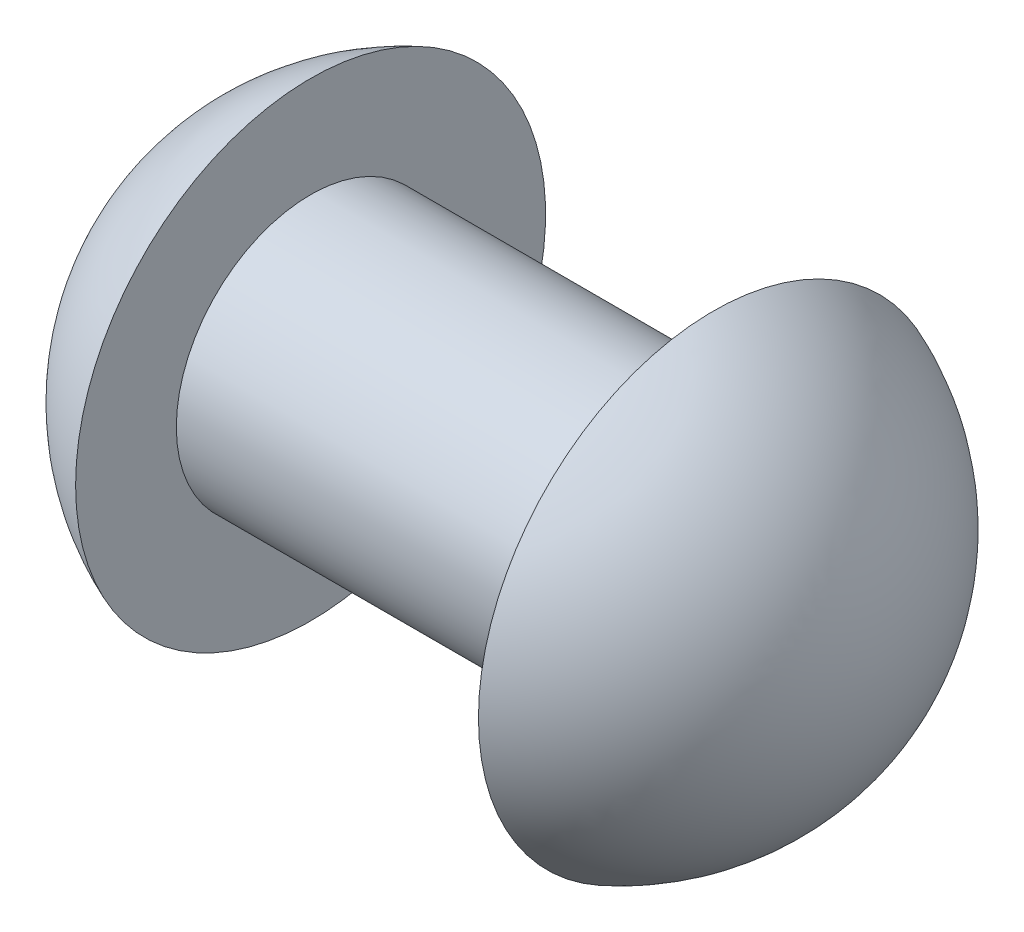
SolidWorks part; units mm, degrees
ref_plane "Plane1" through (0, 0, 0) normal (0, 0, 1) x (1, 0, 0)
ref_plane "Plane2" through (0, 0, 0) normal (0, 1, 0) x (1, 0, 0)
ref_plane "Plane3" through (0, 0, 0) normal (1, 0, 0) x (0, 0, -1)
sketch "Sketch1" plane through (0, 0, 0) normal (0, 0, 1) x (1, 0, 0)
  line L0 (-39, 0) -> (6, 0) construction
  line L1 (-4.2, 0) -> (0, 0)
  line L2 (-3, 1) -> (-3, 1.75)
  line L3 (-3, 1) -> (0, 1)
  line L4 (0, 1) -> (0, 0)
  arc A0 (-3, 1.75) -> (-4.2, 0) centre (-2.3001, -0.0164) ccw
  point P12 (-3, 1)
  dimension "HeadRadius" = 1.9
  dimension "Diameter" = 2
  dimension "GripLength" = 3
  dimension "HeadHt" = 1.2
  dimension "HeadDia" = 3.5
revolve "Base-Revolve" add sketch "Sketch1" angle 360 about L0
sketch "Sketch3" plane through (0, 0, 0) normal (0, 0, 1) x (1, 0, 0)
  line L0 (-49, 0) -> (71, 0) construction
  line L1 (0, 0) -> (1.2, 0)
  line L2 (0, 0) -> (0, 1.75)
  arc A0 (1.2, 0) -> (0, 1.75) centre (-0.6999, -0.0164) ccw
  dimension "D3" = 1.9
  dimension "D1" = 3.5
  dimension "D2" = 1.2
revolve "HeadTypeA" add sketch "Sketch3" angle 360 about L0
sketch "Sketch4" plane through (0, 0, 0) normal (0, 0, 1) x (1, 0, 0)
  line L0 (30, 0) -> (-54, 0) construction
  line L1 (-39, 0) -> (6, 0) construction
  line L2 (0, 0) -> (0, 1.75)
  line L3 (0, 1.75) -> (-0.9774, 1)
  line L4 (-0.9774, 0) -> (0, 0)
  line L5 (0, -1.75) -> (-0.9774, -1) construction
  line L6 (-0.9774, 0) -> (-0.9774, 1)
  dimension "D1" = 3.5
  dimension "D3" = 2
  dimension "D2" = 75
revolve "HeadTypeB" [suppressed] add sketch "Sketch4" angle 360 about L0
scale "Scale1" scale about centroid uniform scaling yes scale factor 0.1
equation "\"D1@Sketch3\" = \"HeadDia@Sketch1\""
equation "\"D2@Sketch3\" = \"HeadHt@Sketch1\""
equation "\"D3@Sketch3\" = \"HeadRadius@Sketch1\""
equation "\"D1@Sketch4\" = \"HeadDia@Sketch1\""
equation "\"D3@Sketch4\" = \"Diameter@Sketch1\""
